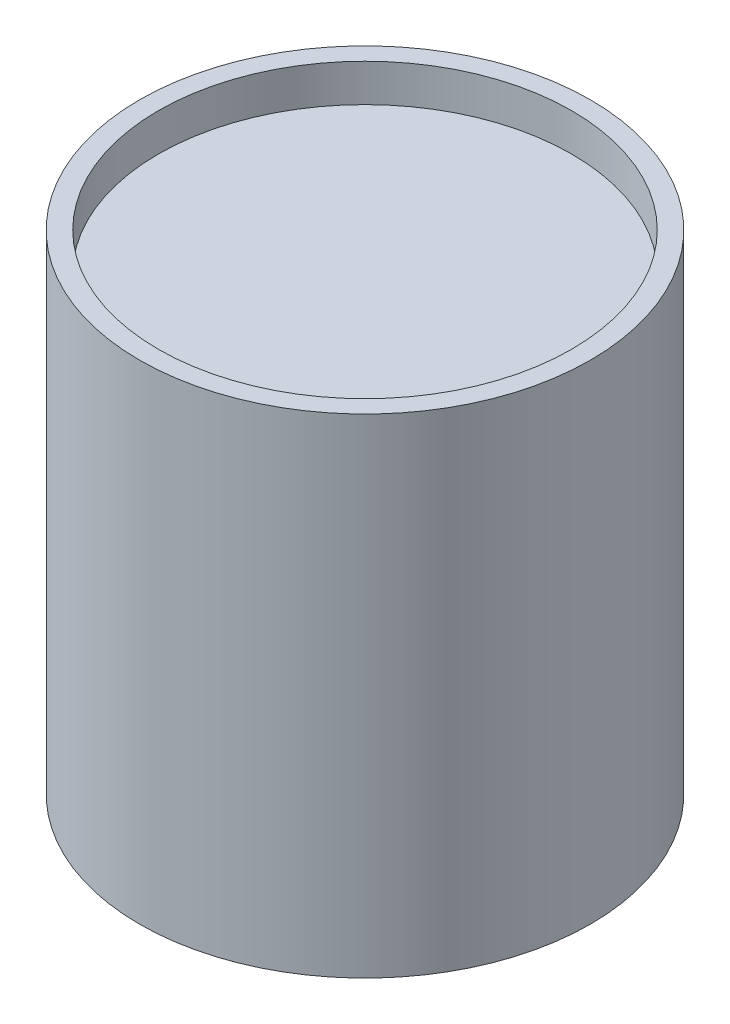
SolidWorks part; units mm, degrees
ref_plane "前视基准面" through (0, 0, 0) normal (0, 0, 1) x (1, 0, 0)
ref_plane "上视基准面" through (0, 0, 0) normal (0, 1, 0) x (1, 0, 0)
ref_plane "右视基准面" through (0, 0, 0) normal (1, 0, 0) x (0, 0, -1)
sketch "草图1" plane through (0, 0, 0) normal (0, 1, 0) x (1, 0, 0)
  circle A0 centre (0, 0) radius 30
  dimension "D1" = 60
extrude "凸台-拉伸1" add sketch "草图1" along normal blind 65
sketch "草图2" plane through (0, 65, 0) normal (0, 1, 0) x (1, 0, 0)
  circle A0 centre (0, 0) radius 27.5
  dimension "D1" = 55
extrude "切除-拉伸1" cut sketch "草图2" against normal blind 5
sketch "草图3" plane through (0, 0, 0) normal (0, -1, 0) x (1, 0, 0)
  circle A0 centre (0, 0) radius 27.5
  dimension "D1" = 55
extrude "切除-拉伸2" cut sketch "草图3" against normal offset from surface (57 mm away) 3 up to face at (0, 60, 27.5)
